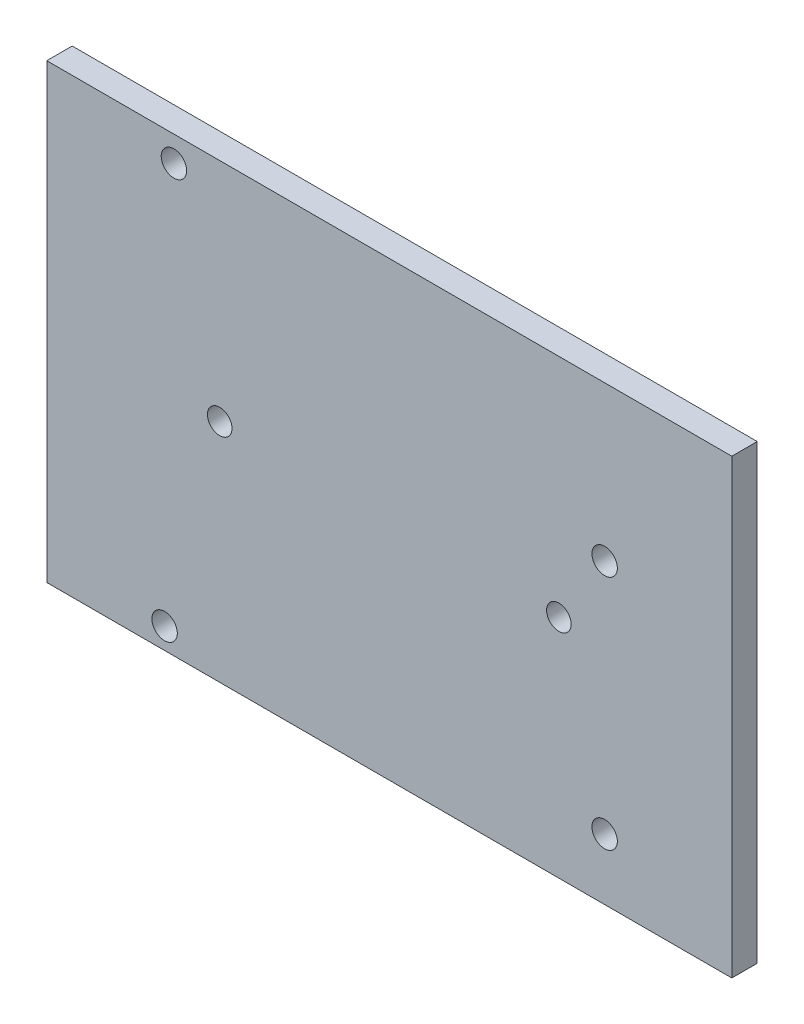
SolidWorks part; units mm, degrees
material "ABS"
ref_plane "Front Plane" through (0, 0, 0) normal (0, 0, 1) x (1, 0, 0)
ref_plane "Top Plane" through (0, 0, 0) normal (0, 1, 0) x (1, 0, 0)
ref_plane "Right Plane" through (0, 0, 0) normal (1, 0, 0) x (0, 0, -1)
sketch "Sketch1" plane through (0, 0, 0) normal (0, 0, 1) x (1, 0, 0)
  line L0 (-40.4, 26.65) -> (40.4, 26.65)
  line L1 (-40.4, 26.65) -> (-40.4, -26.65)
  line L2 (-40.4, -26.65) -> (40.4, -26.65)
  line L8 (40.4, 26.65) -> (40.4, -26.65)
  circle A0 centre (-25.4, 23.65) radius 1.5
  circle A1 centre (-26.5, -24.15) radius 1.5
  circle A2 centre (25.4, -19.45) radius 1.5
  circle A3 centre (25.4, 8.45) radius 1.5
  circle A4 centre (20, 0) radius 1.45
  circle A5 centre (-20, 0) radius 1.45
  point P16 (0, 0)
  dimension "D11" = 2.9
  dimension "D15" = 3
  dimension "D16" = 3
  dimension "D17" = 3
  dimension "D18" = 3
  dimension "D1" = 1.1
  dimension "D2" = 3
  dimension "D3" = 18.2
  dimension "D4" = 50.8
  dimension "D5" = 2.5
  dimension "D6" = 7.2
  dimension "D7" = 51.9
  dimension "D8" = 53.3
  dimension "D9" = 15
  dimension "D10" = 15
  dimension "D12" = 20
  dimension "D13" = 20
  dimension "D14" = 40.4
extrude "Boss-Extrude1" add sketch "Sketch1" along normal blind 3
